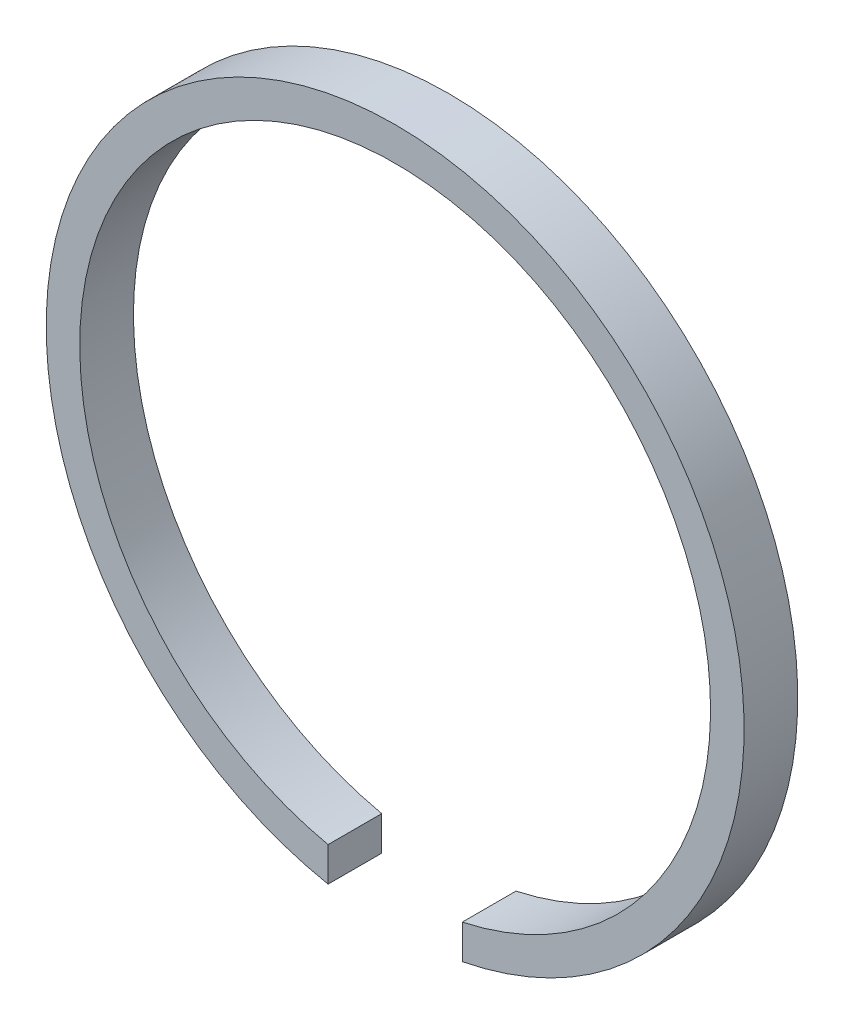
SolidWorks part; units mm, degrees
ref_plane "前视基准面" through (0, 0, 0) normal (0, 0, 1) x (1, 0, 0)
ref_plane "上视基准面" through (0, 0, 0) normal (0, 1, 0) x (1, 0, 0)
ref_plane "右视基准面" through (0, 0, 0) normal (1, 0, 0) x (0, 0, -1)
sketch "草图1" plane through (0, 0, 0) normal (0, 0, 1) x (1, 0, 0)
  line L0 (-5, -22.9619) -> (-5, -25.5147)
  line L1 (5, -25.5147) -> (5, -22.9619)
  line L2 (0, -55) -> (0, 55) construction
  circle A0 centre (0, 0) radius 26
  circle A1 centre (0, 0) radius 23.5
  dimension "D1" = 52
  dimension "D2" = 47
  dimension "D3" = 5
  dimension "D4" = 5
extrude "凸台-拉伸1" add sketch "草图1" along normal blind 4 contours A1 L1 A0 L0
